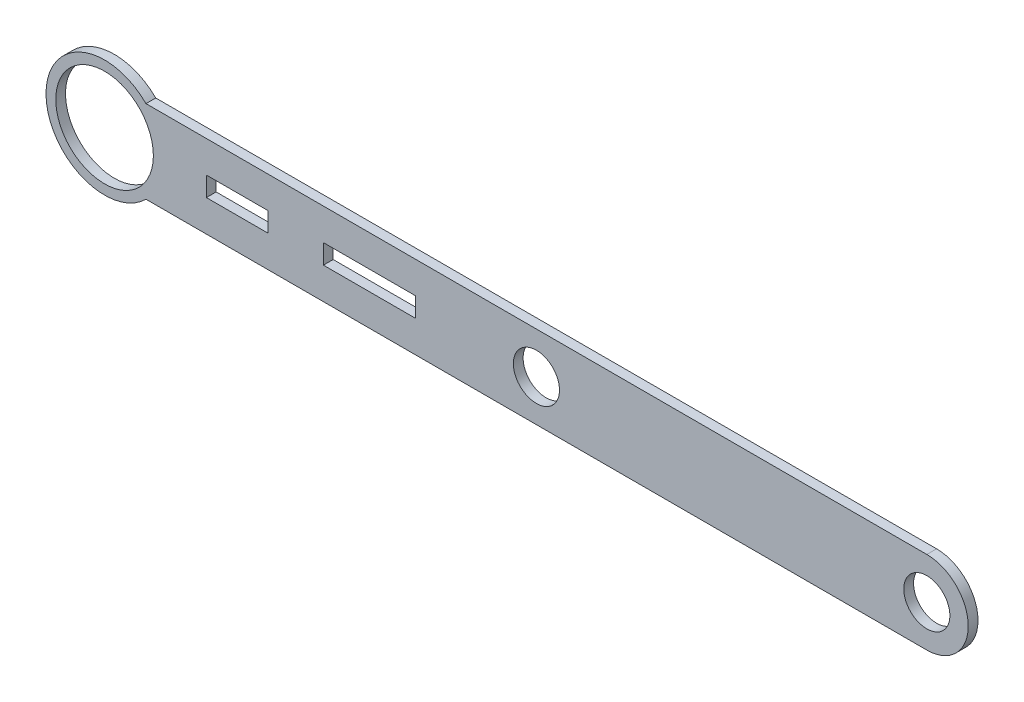
SolidWorks part; units mm, degrees
ref_plane "Front Plane" through (0, 0, 0) normal (0, 0, 1) x (1, 0, 0)
ref_plane "Top Plane" through (0, 0, 0) normal (0, 1, 0) x (1, 0, 0)
ref_plane "Right Plane" through (0, 0, 0) normal (1, 0, 0) x (0, 0, -1)
sketch "Sketch1" plane through (0, 0, 0) normal (0, 0, 1) x (1, 0, 0)
  line L9 (13.4704, 13.4704) -> (267.4704, 13.4704)
  line L10 (13.4704, -13.4704) -> (267.4704, -13.4704)
  line L16 (33.1171, -3.175) -> (53.1171, -3.175)
  line L17 (33.1171, -3.175) -> (33.1171, 3.175)
  line L18 (33.1171, 3.175) -> (53.1171, 3.175)
  line L19 (53.1171, -3.175) -> (53.1171, 3.175)
  line L22 (71.1956, 3.175) -> (101.1956, 3.175)
  line L23 (71.1956, 3.175) -> (71.1956, -3.175)
  line L24 (71.1956, -3.175) -> (101.1956, -3.175)
  line L25 (101.1956, 3.175) -> (101.1956, -3.175)
  circle A1 centre (0, 0) radius 15.875
  arc A4 (13.4704, 13.4704) -> (13.4704, -13.4704) centre (0, 0) ccw
  arc A5 (267.4704, -13.4704) -> (267.4704, 13.4704) centre (267.4704, 0) ccw
  circle A6 centre (267.4704, 0) radius 7.5
  circle A7 centre (140.4704, 0) radius 7.5
  point P7 (0, 0)
  point P12 (268.199, 0.6865)
  point P15 (43.1171, 0)
  point P20 (86.1956, 0)
  dimension "D1" = 15
  dimension "D2" = 15
  dimension "D3" = 20
  dimension "D4" = 6.35
  dimension "D5" = 30
extrude "Boss-Extrude1" add sketch "Sketch1" along normal blind 3.175
